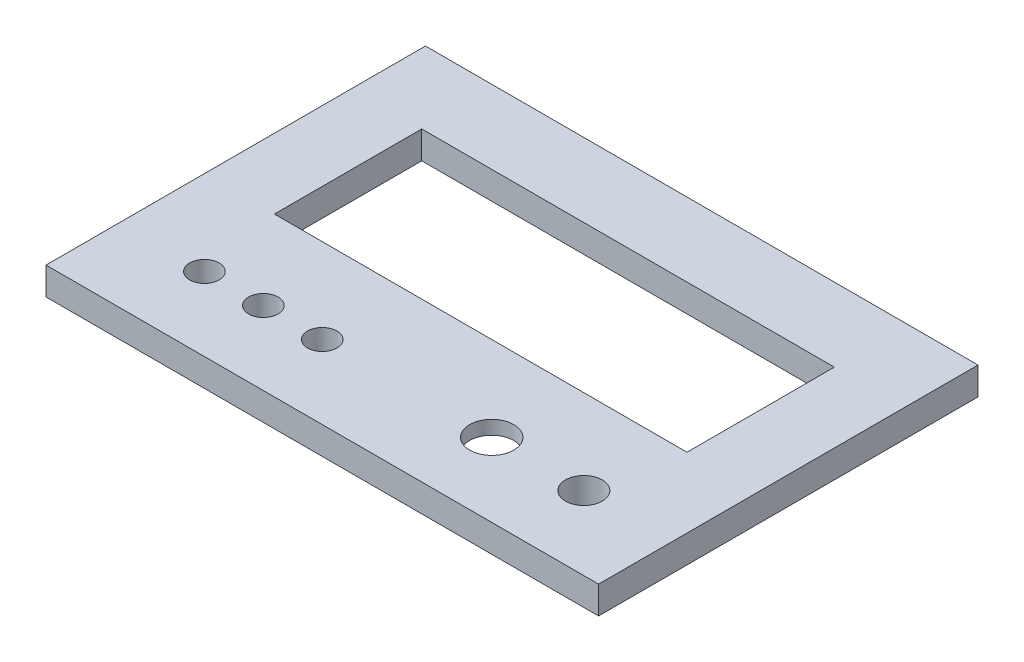
SolidWorks part; units mm, degrees
ref_plane "Front Plane" through (0, 0, 0) normal (0, 0, 1) x (1, 0, 0)
ref_plane "Top Plane" through (0, 0, 0) normal (0, 1, 0) x (1, 0, 0)
ref_plane "Right Plane" through (0, 0, 0) normal (1, 0, 0) x (0, 0, -1)
sketch "Sketch1" plane through (0, 0, 0) normal (0, 1, 0) x (1, 0, 0)
  line L0 (70.485, 6.35) -> (57.785, 6.35) construction
  line L1 (95.25, 0) -> (0, 0)
  line L2 (95.25, 0) -> (95.25, 65.405)
  line L3 (95.25, 65.405) -> (0, 65.405)
  line L4 (0, 0) -> (0, 65.405)
  line L5 (83.185, 52.705) -> (12.065, 52.705)
  line L6 (83.185, 52.705) -> (83.185, 27.305)
  line L7 (83.185, 27.305) -> (12.065, 27.305)
  line L8 (12.065, 52.705) -> (12.065, 27.305)
  line L9 (83.185, 52.705) -> (12.065, 27.305) construction
  line L10 (83.185, 27.305) -> (12.065, 52.705) construction
  line L11 (85.344, 6.604) -> (74.676, 6.604) construction
  line L12 (85.344, 6.604) -> (85.344, 18.796) construction
  line L13 (85.344, 18.796) -> (74.676, 18.796) construction
  line L14 (74.676, 6.604) -> (74.676, 18.796) construction
  line L15 (85.344, 6.604) -> (74.676, 18.796) construction
  line L16 (85.344, 18.796) -> (74.676, 6.604) construction
  line L17 (70.485, 6.35) -> (70.485, 19.05) construction
  line L18 (70.485, 19.05) -> (57.785, 19.05) construction
  line L19 (57.785, 6.35) -> (57.785, 19.05) construction
  line L20 (70.485, 6.35) -> (57.785, 19.05) construction
  line L21 (70.485, 19.05) -> (57.785, 6.35) construction
  line L22 (14.605, 12.7) -> (24.765, 12.7) construction
  line L23 (24.765, 12.7) -> (34.925, 12.7) construction
  line L24 (88.9, 20.955) -> (6.35, 20.955) construction
  line L25 (88.9, 20.955) -> (88.9, 59.055) construction
  line L26 (88.9, 59.055) -> (6.35, 59.055) construction
  line L27 (6.35, 20.955) -> (6.35, 59.055) construction
  line L28 (88.9, 20.955) -> (6.35, 59.055) construction
  line L29 (88.9, 59.055) -> (6.35, 20.955) construction
  line L30 (57.785, 6.35) -> (57.785, 0) construction
  line L31 (12.065, 52.705) -> (0, 52.705) construction
  line L32 (95.25, 52.705) -> (83.185, 52.705) construction
  line L33 (57.785, 19.05) -> (57.785, 20.955) construction
  line L34 (70.485, 65.405) -> (70.485, 59.055) construction
  line L35 (95.25, 59.055) -> (88.9, 59.055) construction
  line L36 (83.185, 27.305) -> (83.185, 0) construction
  line L37 (12.065, 27.305) -> (12.065, 0) construction
  circle A0 centre (34.925, 12.7) radius 2.54
  circle A1 centre (14.605, 12.7) radius 2.54
  circle A2 centre (24.765, 12.7) radius 2.54
  circle A3 centre (80.01, 12.7) radius 3.175
  circle A4 centre (64.135, 12.7) radius 3.81
  point P0 (0, 0)
  point P8 (47.625, 40.005)
  point P19 (47.625, 40.005)
  dimension "D3" = 5.08
  dimension "D8" = 6.35
  dimension "D10" = 7.62
  dimension "D2" = 1.905
  dimension "D4" = 25.4
  dimension "D5" = 71.12
  dimension "D6" = 12.192
  dimension "D7" = 10.668
  dimension "D9" = 12.7
  dimension "D11" = 38.1
  dimension "D12" = 82.55
  dimension "D13" = 6.35
  dimension "D14" = 6.35
  dimension "D15" = 95.25
  dimension "D16" = 65.405
  dimension "D17" = 10.16
  dimension "D18" = 15.875
extrude "Boss-Extrude1" add sketch "Sketch1" along normal blind 4.7625
sketch "Sketch3" plane through (0, 0, 0) normal (0, -1, 0) x (1, 0, 0)
  line L0 (0, -65.405) -> (0, 0) construction
  line L1 (0, -65.405) -> (0, 0)
  line L2 (95.25, 0) -> (95.25, -65.405) construction
  line L3 (95.25, -65.405) -> (0, -65.405) construction
  line L4 (0, 0) -> (95.25, 0) construction
  line L5 (95.25, 0) -> (95.25, -65.405)
  line L6 (95.25, -65.405) -> (0, -65.405)
  line L7 (0, 0) -> (95.25, 0)
  line L8 (3.175, -62.23) -> (3.175, -3.175)
  line L9 (3.175, -3.175) -> (92.075, -3.175)
  line L10 (92.075, -3.175) -> (92.075, -62.23)
  line L11 (92.075, -62.23) -> (3.175, -62.23)
  line L12 (5.715, -59.69) -> (5.715, -5.715)
  line L13 (5.715, -5.715) -> (89.535, -5.715)
  line L14 (89.535, -5.715) -> (89.535, -59.69)
  line L15 (89.535, -59.69) -> (5.715, -59.69)
  dimension "D1" = 3.175
  dimension "D2" = 2.54
extrude "Boss-Extrude2" add sketch "Sketch3" along normal blind 2.54 contours L11 L10 L9 L8 L14 L15 L12 L13
sketch "Sketch2" plane through (0, 0, 0) normal (0, -1, 0) x (1, 0, 0)
  line L1 (71.12, -5.715) -> (57.15, -5.715)
  line L2 (71.12, -5.715) -> (71.12, -19.685)
  line L3 (71.12, -19.685) -> (57.15, -19.685)
  line L4 (57.15, -5.715) -> (57.15, -19.685)
  line L5 (71.12, -5.715) -> (57.15, -19.685) construction
  line L6 (71.12, -19.685) -> (57.15, -5.715) construction
  point P0 (64.135, -12.7)
  dimension "D1" = 13.97
extrude "Cut-Extrude1" cut sketch "Sketch2" against normal blind 2.3813 and the other way through all
